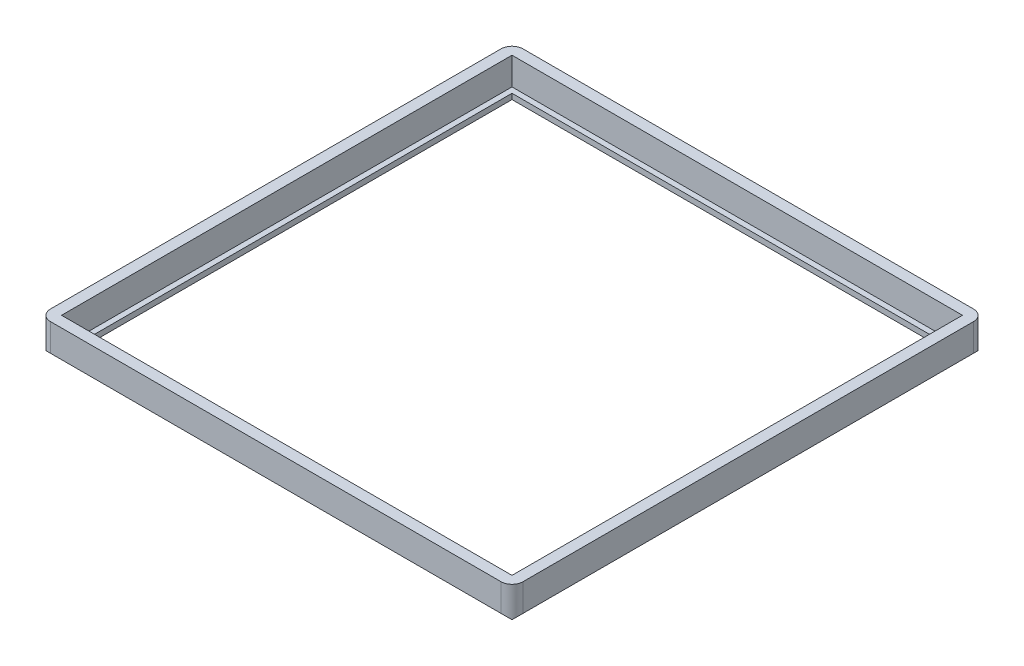
SolidWorks part; units mm, degrees
material "普通碳钢"
ref_plane "前视基准面" through (0, 0, 0) normal (0, 0, 1) x (1, 0, 0)
ref_plane "上视基准面" through (0, 0, 0) normal (0, 1, 0) x (1, 0, 0)
ref_plane "右视基准面" through (0, 0, 0) normal (1, 0, 0) x (0, 0, -1)
sketch "草图1" plane through (0, 0, 0) normal (0, 1, 0) x (1, 0, 0)
  line L1 (-40, -40) -> (40, -40)
  line L2 (-40, -40) -> (-40, 40)
  line L3 (-40, 40) -> (40, 40)
  line L4 (40, -40) -> (40, 40)
  line L5 (-40, -40) -> (40, 40) construction
  line L6 (-40, 40) -> (40, -40) construction
  line L7 (-41, -41) -> (41, -41)
  line L8 (-41, -41) -> (-41, 41)
  line L9 (-41, 41) -> (41, 41)
  line L10 (41, -41) -> (41, 41)
  line L11 (-41, -41) -> (41, 41) construction
  line L12 (-41, 41) -> (41, -41) construction
  line L13 (-43, -43) -> (43, -43)
  line L14 (-43, -43) -> (-43, 43)
  line L15 (-43, 43) -> (43, 43)
  line L16 (43, -43) -> (43, 43)
  line L17 (-43, -43) -> (43, 43) construction
  line L18 (-43, 43) -> (43, -43) construction
  point P0 (0, 0)
  point P6 (0, 0)
  point P11 (0, 0)
  dimension "D1" = 80
  dimension "D2" = 80
  dimension "D3" = 82
  dimension "D4" = 82
  dimension "D5" = 86
  dimension "D6" = 86
extrude "凸台-拉伸1" add sketch "草图1" along normal blind 1 contours L13 L16 L15 L14
sketch "草图2" plane through (0, 0, 0) normal (0, -1, 0) x (1, 0, 0)
  line L1 (-40, 40) -> (40, 40)
  line L2 (-40, 40) -> (-40, -40)
  line L3 (-40, -40) -> (40, -40)
  line L4 (40, 40) -> (40, -40)
  line L5 (-40, 40) -> (40, -40) construction
  line L6 (-40, -40) -> (40, 40) construction
  point P0 (0, 0)
  dimension "D1" = 80
  dimension "D2" = 80
extrude "切除-拉伸1" cut sketch "草图2" against normal through all
sketch "草图3" plane through (0, 1, 0) normal (0, 1, 0) x (1, 0, 0)
  line L1 (-41, 41) -> (41, 41)
  line L2 (-41, 41) -> (-41, -41)
  line L3 (-41, -41) -> (41, -41)
  line L4 (41, 41) -> (41, -41)
  line L5 (-41, 41) -> (41, -41) construction
  line L6 (-41, -41) -> (41, 41) construction
  line L7 (-43, 43) -> (43, 43)
  line L8 (-43, 43) -> (-43, -43)
  line L9 (-43, -43) -> (43, -43)
  line L10 (43, 43) -> (43, -43)
  line L11 (-43, 43) -> (43, -43) construction
  line L12 (-43, -43) -> (43, 43) construction
  point P0 (0, 0)
  point P6 (0, 0)
  dimension "D1" = 82
  dimension "D2" = 82
extrude "凸台-拉伸2" add sketch "草图3" along normal blind 5
chamfer "倒角1" distance 1 angle 45 4 edges at (43, 0, 0) (0, 0, 43) (-43, 0, 0) (0, 0, -43)
fillet "圆角1" radius 2 4 edges at (43, 3.5, 43) (-43, 3.5, 43) (-43, 3.5, -43) (43, 3.5, -43)
